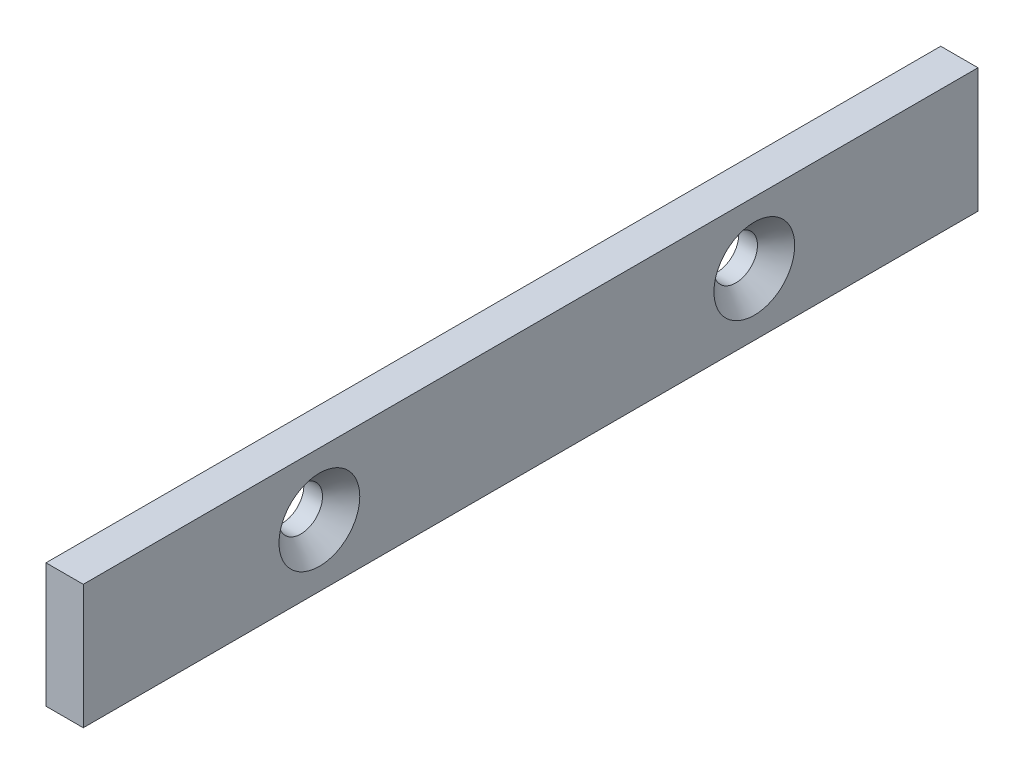
SolidWorks part; units mm, degrees
material "AISI 1020 Steel, Cold Rolled"
ref_plane "Front Plane" through (0, 0, 0) normal (0, 0, 1) x (1, 0, 0)
ref_plane "Top Plane" through (0, 0, 0) normal (0, 1, 0) x (1, 0, 0)
ref_plane "Right Plane" through (0, 0, 0) normal (1, 0, 0) x (0, 0, -1)
sketch "Sketch1" plane through (0, 0, 0) normal (1, 0, 0) x (0, 0, -1)
  line L1 (-72, 10) -> (72, 10)
  line L2 (-72, 10) -> (-72, -10)
  line L3 (-72, -10) -> (72, -10)
  line L4 (72, 10) -> (72, -10)
  line L5 (0, -10) -> (0, 10) construction
  line L6 (-72, 0) -> (72, 0) construction
  circle A0 centre (-34, 0) radius 3.5
  circle A1 centre (36, 0) radius 3.5
  point P0 (0, 0)
  dimension "D3" = 7
  dimension "D4" = 7
  dimension "D1" = 20
  dimension "D2" = 144
  dimension "D5" = 38
  dimension "D6" = 70
extrude "Boss-Extrude1" add sketch "Sketch1" against normal blind 6
chamfer "Chamfer1" distance 3 angle 45 2 edges at (0, 0, -39.5) (0, 0, 30.5)
